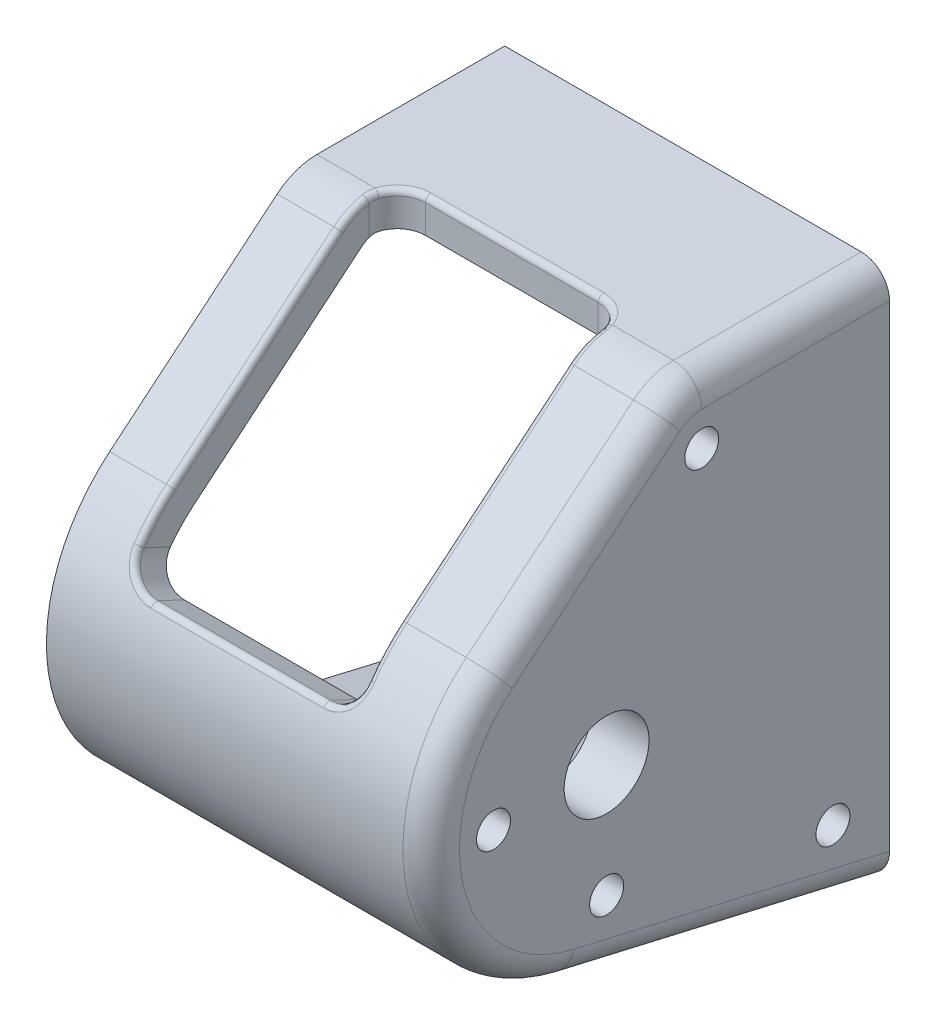
SolidWorks part; units mm, degrees
ref_plane "Front Plane" through (0, 0, 0) normal (0, 0, 1) x (1, 0, 0)
ref_plane "Top Plane" through (0, 0, 0) normal (0, 1, 0) x (1, 0, 0)
ref_plane "Right Plane" through (0, 0, 0) normal (1, 0, 0) x (0, 0, -1)
sketch "Sketch1" plane through (0, 0, 0) normal (0, 1, 0) x (1, 0, 0)
  line L0 (-29, 50) -> (29, -50) construction
  line L2 (-29, -50) -> (-29, 50)
  line L3 (-29, 50) -> (29, 50)
  line L4 (29, -50) -> (29, 50)
  line L8 (-18, 20) -> (22.5, 20)
  line L10 (-18, -50) -> (-18, 20)
  line L15 (22.5, 20) -> (22.5, -50)
  line L16 (-29, -50) -> (-18, -50)
  line L17 (22.5, -50) -> (29, -50)
  point P4 (0, 0)
  dimension "D1" = 58
  dimension "D2" = 100
  dimension "D3" = 30
  dimension "D4" = 6.5
  dimension "D5" = 11
extrude "Boss-Extrude1" add sketch "Sketch1" along normal blind 100
sketch "Sketch5" plane through (29, 0, 0) normal (1, 0, 0) x (0, 0, -1)
  line L0 (50, 94) -> (15, 94)
  line L1 (50, 100) -> (50, 0) construction
  line L2 (15, 94) -> (-15.989, 68.2185)
  line L3 (44, 13) -> (50, 13)
  line L5 (-5.7094, 24.6607) -> (44, 13)
  line L6 (12.8305, 100) -> (-19.8263, 72.831)
  line L7 (-6.9883, 18.798) -> (44, 7)
  line L11 (44, 7) -> (44, 13) construction
  line L12 (-50, 100) -> (50, 100) construction
  line L13 (12.8305, 100) -> (-50, 100)
  line L14 (44, 7) -> (50, 7)
  line L20 (-50, 100) -> (-50, 0)
  line L23 (50, 0) -> (50, 7)
  line L24 (50, 13) -> (50, 94)
  line L25 (-50, 0) -> (50, 0)
  arc A4 (-15.989, 68.2185) -> (-5.7094, 24.6607) centre (0, 49) ccw
  arc A5 (-19.8263, 72.831) -> (-6.9883, 18.798) centre (0, 49) ccw
  point P4 (47, 13)
  dimension "D3" = 50
  dimension "D5" = 50
  dimension "D1" = 35
  dimension "D2" = 6
  dimension "D4" = 45
  dimension "D6" = 81
  dimension "D7" = 6
  dimension "D8" = 6
  dimension "D9" = 6
  dimension "D10" = 6
extrude "Cut-Extrude1" cut sketch "Sketch5" against normal through all
fillet "Fillet1" radius 5 2 edges at (-23.5, 94, -15) (25.75, 94, -15)
sketch "Sketch6" plane through (-18, 0, 0) normal (1, 0, 0) x (0, 0, -1)
  line L4 (44, 7) -> (-6.9883, 18.798) construction
  line L5 (-5.7094, 24.6607) -> (44, 13) construction
  line L6 (20, 12.5533) -> (-6.9883, 18.798)
  line L7 (-5.7094, 24.6607) -> (20, 18.6298)
  line L8 (-22.6577, 59.5655) -> (-28.0955, 62.1012)
  line L9 (20, 18.6298) -> (20, 12.5533)
  line L10 (0, 49) -> (-25, 49) construction
  arc A5 (-19.8263, 72.831) -> (-6.9883, 18.798) centre (0, 49) ccw construction
  arc A6 (-15.989, 68.2185) -> (-5.7094, 24.6607) centre (0, 49) ccw construction
  arc A7 (-28.0955, 62.1012) -> (-6.9883, 18.798) centre (0, 49) ccw
  arc A8 (-22.6577, 59.5655) -> (-5.7094, 24.6607) centre (0, 49) ccw
  dimension "D1" = 25
extrude "Boss-Extrude2" add sketch "Sketch6" along normal up to surface (40.5 mm away) up to face at (22.5, 62.6957, -4.0362)
fillet "Fillet2" radius 11 2 edges at (25.75, 100, -12.8305) (-23.5, 100, -12.8305)
fillet "Fillet3" radius 5 4 edges at (22.5, 60.8333, 25.3766) (-18, 60.8333, 25.3766) (22.5, 97, -20) (-18, 97, -20)
sketch "Sketch7" plane through (29, 0, 0) normal (1, 0, 0) x (0, 0, -1)
  line L10 (50, 100) -> (16.8079, 100)
  line L11 (9.7728, 97.4562) -> (-19.8263, 72.831)
  line L12 (-6.9883, 18.798) -> (44, 7)
  line L13 (44, 7) -> (50, 7)
  line L14 (50, 7) -> (50, 13)
  line L15 (50, 13) -> (44, 13)
  line L16 (44, 13) -> (-5.7094, 24.6607)
  line L17 (-15.989, 68.2185) -> (13.6102, 92.8437)
  line L18 (16.8079, 94) -> (50, 94)
  line L19 (50, 94) -> (50, 100)
  line L20 (50, 100) -> (16.8079, 100)
  line L21 (9.7728, 97.4562) -> (-19.8263, 72.831)
  line L22 (-6.9883, 18.798) -> (44, 7)
  line L23 (44, 7) -> (50, 7)
  line L29 (50, 7) -> (50, 100)
  arc A4 (16.8079, 100) -> (9.7728, 97.4562) centre (16.8079, 89) ccw
  arc A5 (-19.8263, 72.831) -> (-6.9883, 18.798) centre (0, 49) ccw
  arc A6 (-15.989, 68.2185) -> (-5.7094, 24.6607) centre (0, 49) ccw
  arc A7 (16.8079, 94) -> (13.6102, 92.8437) centre (16.8079, 89) ccw
  arc A8 (16.8079, 100) -> (9.7728, 97.4562) centre (16.8079, 89) ccw
  arc A9 (-19.8263, 72.831) -> (-6.9883, 18.798) centre (0, 49) ccw
  dimension "D1" = 0
extrude "Boss-Extrude4" add sketch "Sketch7" along normal blind 10
fillet "Fillet5" radius 1 14 edges at (-18, 99.0008, -12.2272) (-17.7632, 99.9962, -16.5204) (-15.8249, 100, -19.1255) (2.25, 100, -20) (20.3249, 100, -19.1255) (22.4909, 99.8963, -15.3014) (22.5, 99.0008, -12.2272) (22.5, 85.1436, 5.0268) (22.5, 69.8479, 22.9426) (21.4185, 63.7935, 27.2425) (2.25, 62.1012, 28.0955) (-16.1228, 63.0855, 27.6152) (-18, 69.8479, 22.9426) (-18, 85.1436, 5.0268)
fillet "Fillet6" radius 5 5 edges at (39, 12.899, -18.5058) (39, 41.834, 30.1604) (39, 85.1436, 5.0268) (39, 99.3445, -13.0675) (39, 100, -33.404)
sketch "Sketch8" plane through (39, 0, 0) normal (1, 0, 0) x (0, 0, -1)
  circle A0 centre (0, 49) radius 7.5
  arc A1 (-16.6285, 68.9873) -> (-5.8612, 23.6693) centre (0, 49) ccw construction
  dimension "D1" = 15
extrude "Cut-Extrude2" cut sketch "Sketch8" against normal through all
sketch "Sketch9" plane through (39, 0, 0) normal (1, 0, 0) x (0, 0, -1)
  circle A0 centre (40, 19.7446) radius 1.25 construction
  circle A1 centre (0, 29) radius 1.25 construction
  circle A2 centre (-20, 49) radius 1.25 construction
  circle A3 centre (16.8079, 89) radius 1.25 construction
  circle A4 centre (40, 19.7446) radius 1.25
  circle A5 centre (0, 29) radius 1.25
  circle A6 centre (-20, 49) radius 1.25
  circle A7 centre (16.8079, 89) radius 1.25
extrude "Cut-Extrude3" cut sketch "Sketch9" against normal through all
sketch "Sketch10" plane through (39, 0, 0) normal (1, 0, 0) x (0, 0, -1)
  circle A5 centre (16.8079, 89) radius 3
  circle A6 centre (-20, 49) radius 3
  circle A7 centre (0, 29) radius 3
  circle A8 centre (40, 19.7446) radius 3
  dimension "D1" = 6
extrude "Cut-Extrude4" cut sketch "Sketch10" against normal blind 5
